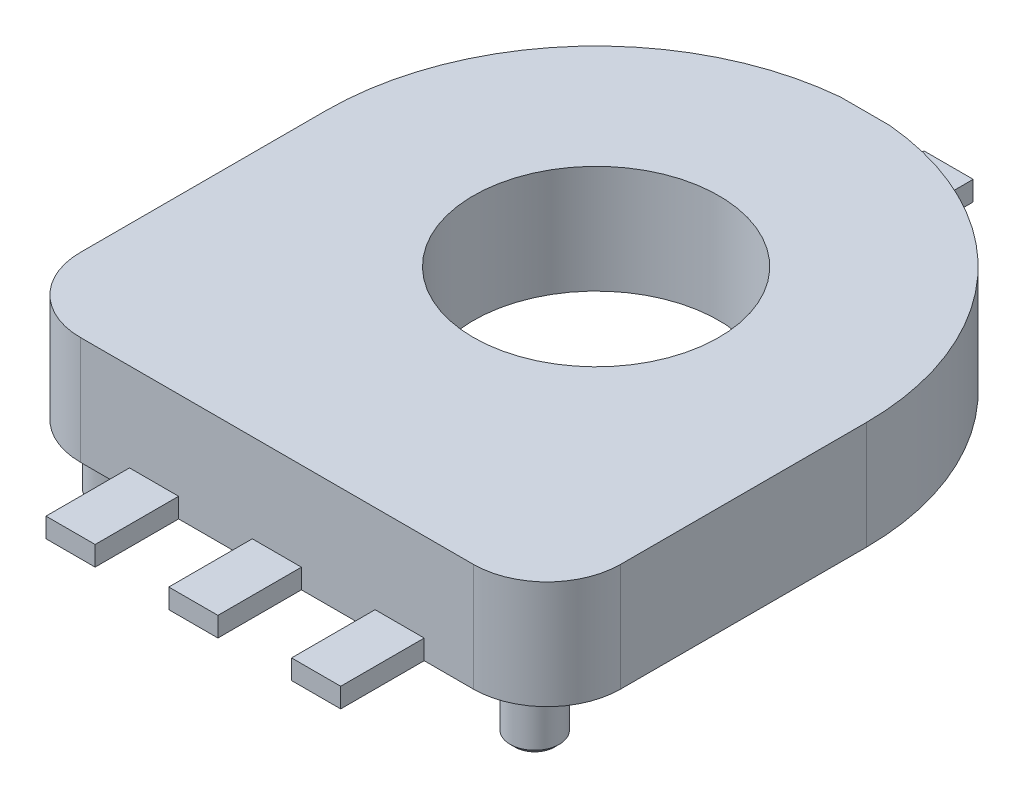
SolidWorks part; units mm, degrees
ref_plane "前视基准面" through (0, 0, 0) normal (0, 0, 1) x (1, 0, 0)
ref_plane "上视基准面" through (0, 0, 0) normal (0, 1, 0) x (1, 0, 0)
ref_plane "右视基准面" through (0, 0, 0) normal (1, 0, 0) x (0, 0, -1)
other "Configuration Table"
sketch "草图1" plane through (0, 0, 0) normal (0, 1, 0) x (1, 0, 0)
  line L0 (0, 1.5) -> (0, 6.5)
  line L1 (11, 6.5) -> (11, 1.5)
  line L2 (9.5, 0) -> (1.5, 0)
  line L3 (5.5, 0) -> (5.5, -1.7) construction
  line L4 (2.5, 0) -> (3.5, 0)
  line L5 (2.5, 0) -> (2.5, -1.7)
  line L6 (2.5, -1.7) -> (3.5, -1.7)
  line L7 (3.5, 0) -> (3.5, -1.7)
  line L8 (5, 0) -> (6, 0)
  line L9 (5, 0) -> (5, -1.7)
  line L10 (5, -1.7) -> (6, -1.7)
  line L11 (6, 0) -> (6, -1.7)
  line L12 (7.5, 0) -> (8.5, 0)
  line L13 (7.5, 0) -> (7.5, -1.7)
  line L14 (7.5, -1.7) -> (8.5, -1.7)
  line L15 (8.5, 0) -> (8.5, -1.7)
  line L17 (6, 13.6772) -> (5, 13.6772)
  line L18 (6, 13.6772) -> (6, 11.9772)
  line L19 (6, 11.9772) -> (5, 11.9772)
  line L20 (5, 13.6772) -> (5, 11.9772)
  arc A0 (0, 6.5) -> (11, 6.5) centre (5.5, 6.5) cw
  arc A1 (11, 1.5) -> (9.5, 0) centre (9.5, 1.5) cw
  arc A2 (0, 1.5) -> (1.5, 0) centre (1.5, 1.5) ccw
  circle A3 centre (5.5, 6.5) radius 2.5
  point P8 (11, 0)
  point P11 (0, 0)
  point P26 (5.5, -1.7)
  point P27 (5.5, 0)
  dimension "D3" = 1.5
  dimension "D4" = 5
  dimension "D1" = 11
  dimension "D2" = 6.5
  dimension "D5" = 6
  dimension "D6" = 1
  dimension "D7" = 8.2
extrude "凸台-拉伸1" add sketch "草图1" along normal mid plane 2.2 contours L0 A2 L2 L8 A1 L1 A0 A3 | L15 L2 L13 L14 | L2 L3 L10 L11 | L3 L8 L9 L10 | L7 L2 L5 L6 | L20 A0 L18 L17 | A0 L19
sketch "草图2" plane through (0, 1.1, 0) normal (0, 1, 0) x (1, 0, 0)
  line L3 (0, 6.5) -> (0, 1.5)
  line L4 (11, 1.5) -> (11, 6.5)
  line L5 (1.5, 0) -> (9.5, 0)
  line L6 (0, 6.5) -> (0, 1.5)
  line L7 (11, 1.5) -> (11, 6.5)
  line L8 (1.5, 0) -> (9.5, 0)
  line L10 (8.5, 0) -> (7.5, 0)
  line L11 (8.5, -1.7) -> (8.5, 0)
  line L12 (7.5, -1.7) -> (8.5, -1.7)
  line L13 (7.5, 0) -> (7.5, -1.7)
  line L14 (8.5, 0) -> (7.5, 0)
  line L15 (8.5, -1.7) -> (8.5, 0)
  line L16 (7.5, -1.7) -> (8.5, -1.7)
  line L17 (7.5, 0) -> (7.5, -1.7)
  line L18 (5, 0) -> (5, -1.7)
  line L19 (5, -1.7) -> (6, -1.7)
  line L20 (6, -1.7) -> (6, 0)
  line L21 (6, 0) -> (7.5, 0)
  line L22 (7.5, 0) -> (7.5, -1.7)
  line L23 (7.5, -1.7) -> (8.5, -1.7)
  line L24 (8.5, -1.7) -> (8.5, 0)
  line L25 (8.5, 0) -> (9.5, 0)
  line L26 (11, 1.5) -> (11, 6.5)
  line L27 (6, 11.9772) -> (6, 13.6772)
  line L28 (6, 13.6772) -> (5, 13.6772)
  line L29 (5, 13.6772) -> (5, 11.9772)
  line L30 (0, 6.5) -> (0, 1.5)
  line L31 (1.5, 0) -> (2.5, 0)
  line L32 (2.5, 0) -> (2.5, -1.7)
  line L33 (2.5, -1.7) -> (3.5, -1.7)
  line L34 (3.5, -1.7) -> (3.5, 0)
  line L35 (3.5, 0) -> (5, 0)
  line L36 (5, 0) -> (5, -1.7)
  line L37 (5, -1.7) -> (6, -1.7)
  line L38 (6, -1.7) -> (6, 0)
  line L39 (6, 0) -> (7.5, 0)
  line L40 (7.5, 0) -> (7.5, -1.7)
  line L41 (7.5, -1.7) -> (8.5, -1.7)
  line L42 (8.5, -1.7) -> (8.5, 0)
  line L43 (8.5, 0) -> (9.5, 0)
  line L44 (11, 1.5) -> (11, 6.5)
  line L45 (6, 11.9772) -> (6, 13.6772)
  line L46 (6, 13.6772) -> (5, 13.6772)
  line L47 (5, 13.6772) -> (5, 11.9772)
  line L48 (0, 6.5) -> (0, 1.5)
  line L49 (1.5, 0) -> (2.5, 0)
  line L50 (2.5, 0) -> (2.5, -1.7)
  line L51 (2.5, -1.7) -> (3.5, -1.7)
  line L52 (3.5, -1.7) -> (3.5, 0)
  line L53 (3.5, 0) -> (5, 0)
  line L54 (6, 0) -> (5, 0)
  line L55 (6, -1.7) -> (6, 0)
  line L56 (5, -1.7) -> (6, -1.7)
  line L57 (5, 0) -> (5, -1.7)
  line L58 (6, 0) -> (5, 0)
  line L59 (6, -1.7) -> (6, 0)
  line L60 (5, -1.7) -> (6, -1.7)
  line L61 (5, 0) -> (5, -1.7)
  line L62 (3.5, 0) -> (2.5, 0)
  line L63 (2.5, 0) -> (2.5, -1.7)
  line L64 (2.5, -1.7) -> (3.5, -1.7)
  line L65 (3.5, -1.7) -> (3.5, 0)
  line L66 (3.5, 0) -> (2.5, 0)
  line L67 (2.5, 0) -> (2.5, -1.7)
  line L68 (2.5, -1.7) -> (3.5, -1.7)
  line L69 (3.5, -1.7) -> (3.5, 0)
  line L70 (6, 13.6772) -> (5, 13.6772)
  line L71 (6, 11.9772) -> (6, 13.6772)
  line L72 (5, 11.9772) -> (6, 11.9772)
  line L73 (5, 13.6772) -> (5, 11.9772)
  line L74 (6, 13.6772) -> (5, 13.6772)
  line L75 (6, 11.9772) -> (6, 13.6772)
  line L76 (5, 11.9772) -> (6, 11.9772)
  line L77 (5, 13.6772) -> (5, 11.9772)
  circle A0 centre (5.5, 6.5) radius 2.5 construction
  circle A1 centre (5.5, 6.5) radius 2.5
  circle A3 centre (5.5, 6.5) radius 2.5
  arc A4 (9.5, 0) -> (11, 1.5) centre (9.5, 1.5) ccw
  arc A5 (11, 6.5) -> (6, 11.9772) centre (5.5, 6.5) ccw
  arc A6 (5, 11.9772) -> (0, 6.5) centre (5.5, 6.5) ccw
  arc A7 (0, 1.5) -> (1.5, 0) centre (1.5, 1.5) ccw
  arc A8 (9.5, 0) -> (11, 1.5) centre (9.5, 1.5) ccw
  arc A9 (11, 6.5) -> (6, 11.9772) centre (5.5, 6.5) ccw
  arc A10 (5, 11.9772) -> (0, 6.5) centre (5.5, 6.5) ccw
  arc A11 (0, 1.5) -> (1.5, 0) centre (1.5, 1.5) ccw
  circle A12 centre (5.5, 6.5) radius 2.5
  arc A15 (11, 6.5) -> (0, 6.5) centre (5.5, 6.5) ccw
  arc A16 (9.5, 0) -> (11, 1.5) centre (9.5, 1.5) ccw
  arc A17 (0, 1.5) -> (1.5, 0) centre (1.5, 1.5) ccw
  arc A18 (11, 6.5) -> (0, 6.5) centre (5.5, 6.5) ccw
  arc A19 (9.5, 0) -> (11, 1.5) centre (9.5, 1.5) ccw
  arc A20 (0, 1.5) -> (1.5, 0) centre (1.5, 1.5) ccw
  line M46 (5, 0) -> (5, -1.7)
  line M47 (5, -1.7) -> (6, -1.7)
  line M48 (6, -1.7) -> (6, 0)
  line M50 (7.5, 0) -> (7.5, -1.7)
  line M51 (7.5, -1.7) -> (8.5, -1.7)
  line M52 (8.5, -1.7) -> (8.5, 0)
  line M57 (6, 11.9772) -> (6, 13.6772)
  line M58 (6, 13.6772) -> (5, 13.6772)
  line M59 (5, 13.6772) -> (5, 11.9772)
  line M64 (2.5, 0) -> (2.5, -1.7)
  line M65 (2.5, -1.7) -> (3.5, -1.7)
  line M66 (3.5, -1.7) -> (3.5, 0)
  dimension "D1" = 0
  dimension "D2" = 0
  dimension "D3" = 0
  dimension "D4" = 0
  dimension "D5" = 0
  dimension "D6" = 0
  dimension "D7" = 0
extrude "切除-拉伸1" cut sketch "草图2" against normal blind 1.8 contours L8 M50 M51 M52 | L8 M46 M47 M48 | L8 M64 M65 M66 | L76 A18 | A18 M57 M58 M59 | L45 L46 L47 A10 L48 A11 L49 L50 L51 L52 L53 L36 L37 L38 L39 L40 L41 L42 L43 A8 L44 A9
sketch "草图3" plane through (0, -1.1, 0) normal (0, -1, 0) x (1, 0, 0)
  line L0 (5.5, -13.6772) -> (5.5, -4) construction
  line L1 (6, -13.6772) -> (5, -13.6772) construction
  circle A0 centre (1.25, -1) radius 0.5
  circle A1 centre (9.75, -1) radius 0.5
  circle A2 centre (5.5, -6.5) radius 2.5 construction
  dimension "D1" = 1
  dimension "D3" = 5.5
  dimension "D2" = 8.5
extrude "凸台-拉伸2" add sketch "草图3" along normal blind 1.2
chamfer "倒角1" distance 0.1 angle 45 2 edges at (1.25, -2.3, -1.5) (9.75, -2.3, -1.5)
